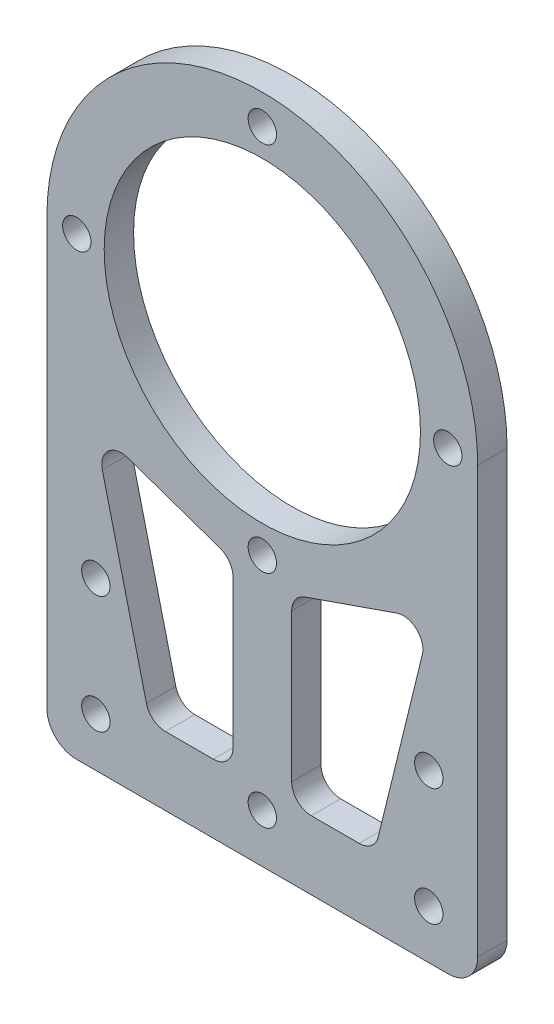
SolidWorks part; units mm, degrees
material "Thornel Mat VMA"
ref_plane "前视基准面" through (0, 0, 0) normal (0, 0, 1) x (1, 0, 0)
ref_plane "上视基准面" through (0, 0, 0) normal (0, 1, 0) x (1, 0, 0)
ref_plane "右视基准面" through (0, 0, 0) normal (1, 0, 0) x (0, 0, -1)
sketch "草图1" plane through (0, 0, 0) normal (0, 0, 1) x (1, 0, 0)
  line L0 (-22, 0) -> (-22, -46.5)
  line L1 (-22, -46.5) -> (22, -46.5)
  line L2 (22, -46.5) -> (22, 0)
  circle A0 centre (0, 0) radius 16.15
  arc A1 (-22, 0) -> (22, 0) centre (0, 0) cw
  dimension "D1" = 32.3
  dimension "D2" = 22
  dimension "D3" = 46.5
extrude "凸台-拉伸1" add sketch "草图1" along normal blind 3
sketch "草图2" plane through (0, 0, 3) normal (0, 0, 1) x (1, 0, 0)
  line L0 (-22, -46.5) -> (22, -46.5) construction
  line L1 (0, -41.5) -> (0, -46.5) construction
  line L2 (0, 17.5) -> (0, 0) construction
  line L3 (22, -46.5) -> (22, 0) construction
  line L4 (-22, 0) -> (-22, -46.5) construction
  circle A0 centre (0, -41.5) radius 1.45
  circle A1 centre (17, -41.5) radius 1.45
  circle A2 centre (-17, -41.5) radius 1.45
  circle A3 centre (0, 0) radius 17.5 construction
  circle A4 centre (0, 18.95) radius 1.45
  circle A5 centre (18.95, 0) radius 1.45
  circle A6 centre (0, -18.95) radius 1.45
  circle A7 centre (-18.95, 0) radius 1.45
  circle A8 centre (-17, -29.5) radius 1.45
  circle A9 centre (17, -29.5) radius 1.45
  dimension "D1" = 2.9
  dimension "D2" = 2.9
  dimension "D3" = 2.9
  dimension "D4" = 5
  dimension "D5" = 5
  dimension "D6" = 5
  dimension "D7" = 17
  dimension "D8" = 17
  dimension "D9" = 35
  dimension "D10" = 2.9
  dimension "D12" = 2.9
  dimension "D13" = 2.9
  dimension "D14" = 5
  dimension "D15" = 5
  dimension "D16" = 12
  dimension "D17" = 12
  dimension "D11" = 4
extrude "切除-拉伸1" cut sketch "草图2" against normal blind 5
fillet "圆角1" radius 3 2 edges at (-22, -46.5, 1.5) (22, -46.5, 1.5)
sketch "草图3" plane through (0, 0, 0) normal (0, 0, -1) x (-1, 0, 0)
  line L0 (-17.2171, -16.0021) -> (-3, -20.95)
  line L1 (-3, -20.95) -> (-3, -39.5)
  line L2 (-3, -39.5) -> (-11.4622, -39.5)
  line L3 (-11.4622, -39.5) -> (-17.2171, -16.0021)
  line L4 (17.2171, -16.0021) -> (3, -20.95)
  line L5 (3, -20.95) -> (3, -39.5)
  line L6 (3, -39.5) -> (11.4622, -39.5)
  line L7 (11.4622, -39.5) -> (17.2171, -16.0021)
  circle A0 centre (0, -18.95) radius 1.45 construction
  circle A1 centre (0, -41.5) radius 1.45 construction
  circle A2 centre (-17, -29.5) radius 1.45 construction
  circle A3 centre (17, -29.5) radius 1.45 construction
  dimension "D1" = 3
  dimension "D2" = 3
  dimension "D4" = 2
  dimension "D5" = 2
  dimension "D6" = 2
  dimension "D3" = 2
  dimension "D7" = 3
  dimension "D8" = 3
extrude "切除-拉伸2" cut sketch "草图3" against normal through all
fillet "圆角2" radius 2 8 edges at (-11.4622, -39.5, 1.5) (-3, -39.5, 1.5) (-3, -20.95, 1.5) (3, -20.95, 1.5) (3, -39.5, 1.5) (11.4622, -39.5, 1.5) (17.2171, -16.0021, 1.5) (-17.2171, -16.0021, 1.5)
